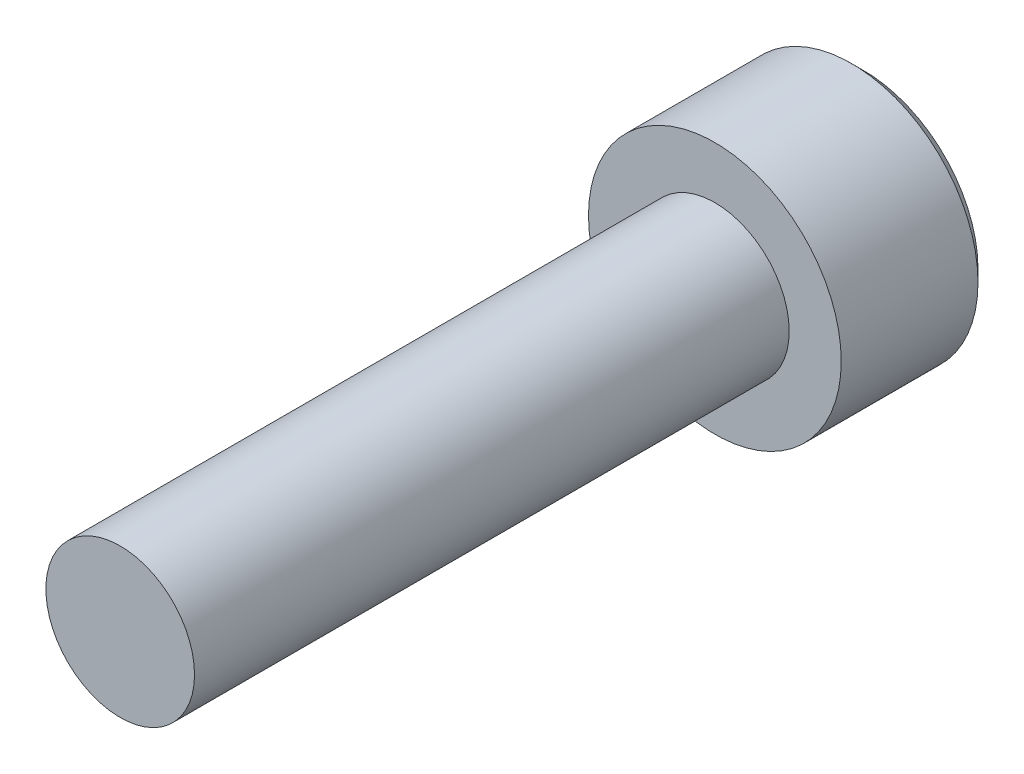
SolidWorks part; units mm, degrees
ref_plane "前视基准面" through (0, 0, 0) normal (0, 0, 1) x (1, 0, 0)
ref_plane "上视基准面" through (0, 0, 0) normal (0, 1, 0) x (1, 0, 0)
ref_plane "右视基准面" through (0, 0, 0) normal (1, 0, 0) x (0, 0, -1)
other "Configuration Table"
sketch "Sk_shank" plane through (0, 0, 0) normal (0, 0, 1) x (1, 0, 0)
  circle A0 centre (0, 0) radius 2.5
extrude "Ext_shank" add sketch "Sk_shank" along normal blind 25
sketch "Sk_head" plane through (0, 0, 0) normal (0, 0, 1) x (1, 0, 0)
  circle A0 centre (0, 0) radius 4.25
extrude "Ext_head" add sketch "Sk_head" along normal blind 5
sketch "Sk_hex" plane through (0, 0, 0) normal (0, 0, 1) x (1, 0, 0)
  line L0 (2.3094, 0) -> (1.1547, 2)
  line L1 (1.1547, 2) -> (-1.1547, 2)
  line L2 (-1.1547, 2) -> (-2.3094, 0)
  line L3 (-2.3094, 0) -> (-1.1547, -2)
  line L4 (-1.1547, -2) -> (1.1547, -2)
  line L5 (1.1547, -2) -> (2.3094, 0)
extrude "Cut_hex" cut sketch "Sk_hex" along normal blind 3
chamfer "Chamfer_head" distance 0.4 angle 45 7 edges at (0, -2, 0) (-1.7321, -1, 0) (-1.7321, 1, 0) (0, 2, 0) (1.7321, 1, 0) (1.7321, -1, 0) (4.25, 0, 0)
